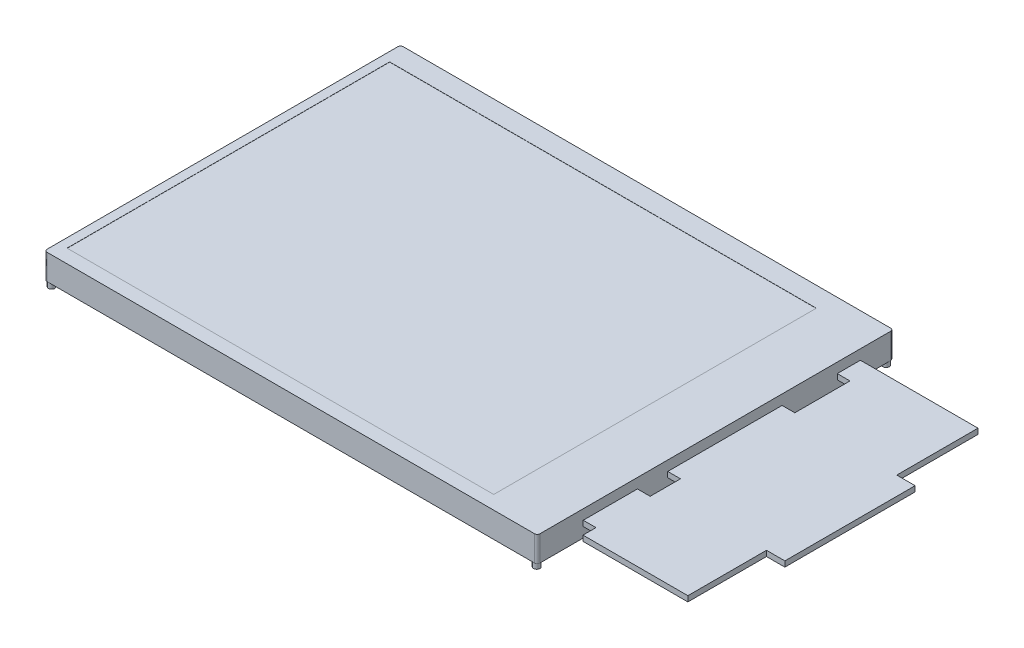
SolidWorks part; units mm, degrees
ref_plane "Front Plane" through (0, 0, 0) normal (0, 0, 1) x (1, 0, 0)
ref_plane "Top Plane" through (0, 0, 0) normal (0, 1, 0) x (1, 0, 0)
ref_plane "Right Plane" through (0, 0, 0) normal (1, 0, 0) x (0, 0, -1)
sketch "Sketch1" plane through (0, 0, 0) normal (0, 1, 0) x (1, 0, 0)
  line L1 (-34.5186, -24.9428) -> (34.5186, -24.9428)
  line L2 (-34.5186, -24.9428) -> (-34.5186, 24.9428)
  line L3 (-34.5186, 24.9428) -> (34.5186, 24.9428)
  line L4 (34.5186, -24.9428) -> (34.5186, 24.9428)
  line L5 (-34.5186, -24.9428) -> (34.5186, 24.9428) construction
  line L6 (-34.5186, 24.9428) -> (34.5186, -24.9428) construction
  point P0 (0, 0)
  dimension "D1" = 69.0372
  dimension "D2" = 49.8856
extrude "Boss-Extrude1" add sketch "Sketch1" along normal mid plane 3.556
fillet "Fillet1" radius 0.381 4 edges at (-34.5186, 0, 24.9428) (34.5186, 0, 24.9428) (34.5186, 0, -24.9428) (-34.5186, 0, -24.9428)
sketch "Sketch2" plane through (0, 1.778, 0) normal (0, 1, 0) x (1, 0, 0)
  line L0 (34.1376, 24.9428) -> (-34.1376, 24.9428) construction
  line L1 (26.5176, -23.0378) -> (-33.2486, -23.0378)
  line L2 (26.5176, -23.0378) -> (26.5176, 22.1488)
  line L3 (26.5176, 22.1488) -> (-33.2486, 22.1488)
  line L4 (-33.2486, -23.0378) -> (-33.2486, 22.1488)
  line L5 (-34.1376, -24.9428) -> (34.1376, -24.9428) construction
  line L6 (-34.5186, 24.5618) -> (-34.5186, -24.5618) construction
  line L7 (34.5186, -24.5618) -> (34.5186, 24.5618) construction
  dimension "D1" = 2.794
  dimension "D2" = 1.905
  dimension "D3" = 1.27
  dimension "D4" = 8.001
extrude "Cut-Extrude1" cut sketch "Sketch2" against normal blind 0.0254
sketch "Sketch3" plane through (0, -1.778, 0) normal (0, -1, 0) x (1, 0, 0)
  line L0 (-33.9725, 24.9174) -> (-33.9725, -24.9174) construction
  line L1 (-34.417, -24.4729) -> (34.417, -24.4729) construction
  line L2 (55, 0) -> (-55, 0) construction
  line L3 (0, -55) -> (0, 55) construction
  line L4 (-34.417, 24.4729) -> (34.417, 24.4729) construction
  circle A0 centre (-33.9725, 24.4729) radius 0.4445
  circle A1 centre (33.9725, 24.4729) radius 0.4445
  circle A2 centre (33.9725, -24.4729) radius 0.4445
  circle A3 centre (-33.9725, -24.4729) radius 0.4445
  point P12 (-33.9725, 0)
  point P17 (0, -24.4729)
  point P20 (0, 24.4729)
  dimension "D1" = 0.889
  dimension "D2" = 49.8348
  dimension "D3" = 68.834
extrude "Boss-Extrude2" add sketch "Sketch3" along normal blind 0.762
sketch "Sketch5" plane through (0, 0, 0) normal (0, 1, 0) x (1, 0, 0)
  line L0 (34.5186, -24.5618) -> (34.5186, 24.5618) construction
  line L1 (34.5186, 20.32) -> (53.5686, 20.32)
  line L2 (34.5186, 20.32) -> (34.5186, -20.32)
  line L3 (34.5186, -20.32) -> (53.5686, -20.32)
  line L4 (53.5686, 20.32) -> (53.5686, -20.32)
  line L5 (-55, 0) -> (55, 0) construction
  point P6 (34.5186, 0)
  dimension "D1" = 40.64
  dimension "D2" = 19.05
extrude "Boss-Extrude3" add sketch "Sketch5" along normal mid plane 0.762
sketch "Sketch6" plane through (0, 0.381, 0) normal (0, 1, 0) x (1, 0, 0)
  line L0 (34.5186, -24.5618) -> (34.5186, 24.5618) construction
  line L1 (53.5686, 20.32) -> (50.9966, 20.32)
  line L2 (53.5686, 20.32) -> (53.5686, 8.9362)
  line L3 (53.5686, 8.9362) -> (50.9966, 8.9362)
  line L4 (50.9966, 20.32) -> (50.9966, 8.9362)
  line L5 (53.5686, -20.32) -> (50.9966, -20.32)
  line L6 (53.5686, -20.32) -> (53.5686, -9.3083)
  line L7 (53.5686, -9.3083) -> (50.9966, -9.3083)
  line L8 (50.9966, -20.32) -> (50.9966, -9.3083)
  line L9 (34.5186, -20.32) -> (36.3035, -20.32)
  line L10 (34.5186, -20.32) -> (34.5186, -18.5002)
  line L11 (34.5186, -18.5002) -> (36.3035, -18.5002)
  line L12 (36.3035, -20.32) -> (36.3035, -18.5002)
  line L13 (34.5186, -6.6622) -> (36.3035, -6.6622)
  line L14 (34.5186, -6.6622) -> (34.5186, -10.9099)
  line L15 (34.5186, -10.9099) -> (36.3035, -10.9099)
  line L16 (36.3035, -6.6622) -> (36.3035, -10.9099)
  line L18 (34.5186, 17.0836) -> (36.3035, 17.0836)
  line L19 (34.5186, 17.0836) -> (34.5186, 9.354)
  line L20 (34.5186, 9.354) -> (36.3035, 9.354)
  line L21 (36.3035, 17.0836) -> (36.3035, 9.354)
extrude "Cut-Extrude2" cut sketch "Sketch6" against normal through all
